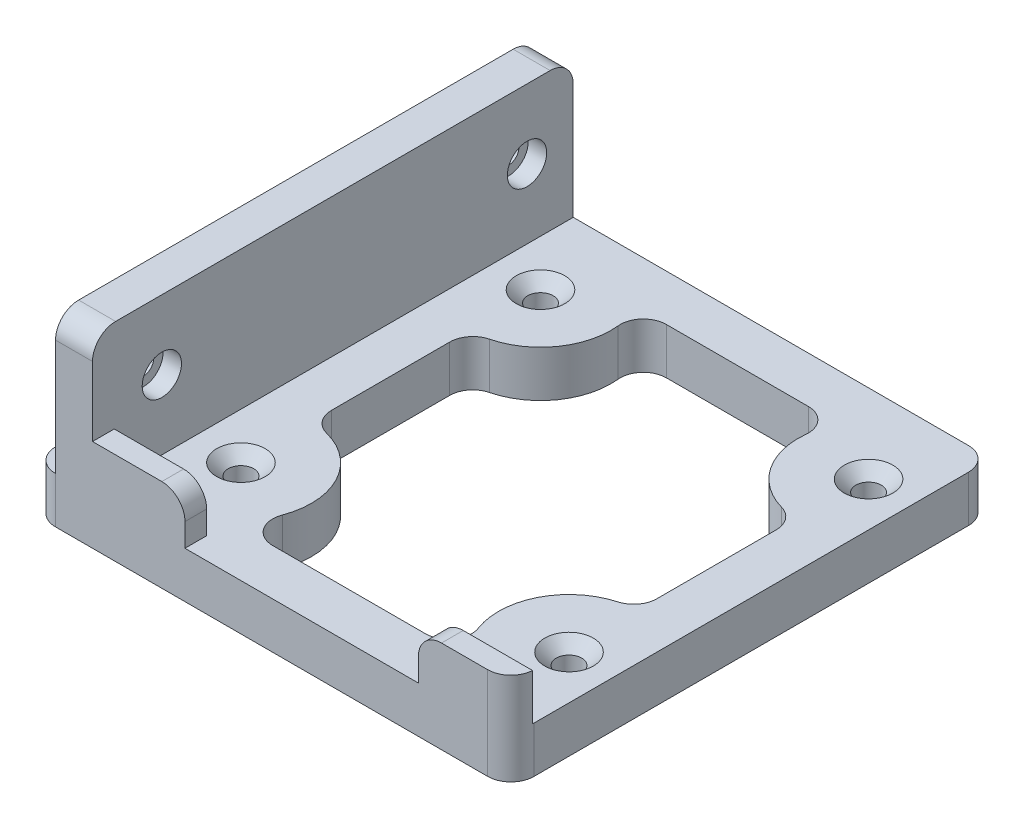
SolidWorks part; units mm, degrees
ref_plane "正面" through (0, 0, 0) normal (0, 0, 1) x (1, 0, 0)
ref_plane "平面" through (0, 0, 0) normal (0, 1, 0) x (1, 0, 0)
ref_plane "右側面" through (0, 0, 0) normal (1, 0, 0) x (0, 0, -1)
sketch "ｽｹｯﾁ1" plane through (0, 0, 0) normal (1, 0, 0) x (0, 0, -1)
  line L4 (0, 21.9) -> (0, -21.9) construction
  point P0 (0, 0)
  line B0 (49.5, -15.9) -> (49.5, 15.9)
  line B1 (-43.5, -21.9) -> (43.5, -21.9)
  line B2 (-49.5, 15.9) -> (-49.5, -15.9)
  line B3 (43.5, 21.9) -> (-43.5, 21.9)
  arc B4 (49.5, 15.9) -> (43.5, 21.9) centre (43.5, 15.9) ccw
  arc B5 (43.5, -21.9) -> (49.5, -15.9) centre (43.5, -15.9) ccw
  arc B6 (-49.5, -15.9) -> (-43.5, -21.9) centre (-43.5, -15.9) ccw
  arc B7 (-43.5, 21.9) -> (-49.5, 15.9) centre (-43.5, 15.9) ccw
sketch_block_instance "ﾌﾞﾛｯｸ2-1"
sketch_block "ﾌﾞﾛｯｸ2"
sketch "ｽｹｯﾁ2" plane through (0, 0, 0) normal (0, 1, 0) x (1, 0, 0)
  line L0 (-49, 48.5) -> (-49, -48.5)
  line L1 (40, 49.5) -> (-48, 49.5)
  line L2 (41, 48.5) -> (41, -48.5)
  line L3 (-49, 0) -> (41, 0) construction
  line L4 (-4, 49.5) -> (-4, -54.5) construction
  line L5 (40, -49.5) -> (-48, -49.5)
  line L6 (41, -43.5) -> (41, 43.5) construction
  line L7 (-39.485, 32.4) -> (31.485, 32.4) construction
  line L8 (-39.485, 32.4) -> (-39.485, -32.4) construction
  line L9 (-39.485, -32.4) -> (31.485, -32.4) construction
  line L10 (31.485, 32.4) -> (31.485, -32.4) construction
  line L11 (-49, -43.5) -> (-49, 43.5) construction
  line L12 (-37, 49.5) -> (-32.97, 49.5) construction
  line L13 (-41, -49.5) -> (-37, -49.5) construction
  line L14 (-48, -43.5) -> (-48, -49.5) construction
  line L15 (-49, -54.5) -> (41, -54.5) construction
  arc A0 (-49, -48.5) -> (-48, -49.5) centre (-48, -48.5) ccw
  arc A1 (-48, 49.5) -> (-49, 48.5) centre (-48, 48.5) ccw
  arc A2 (41, 48.5) -> (40, 49.5) centre (40, 48.5) ccw
  arc A3 (40, -49.5) -> (41, -48.5) centre (40, -48.5) ccw
  circle A4 centre (-39.485, 32.4) radius 2.65 construction
  circle A5 centre (31.485, 32.4) radius 2.65 construction
  arc A6 (41, 48.5) -> (40, 49.5) centre (40, 48.5) ccw construction
  arc A7 (-48, 49.5) -> (-49, 48.5) centre (-48, 48.5) ccw construction
  circle A8 centre (31.485, 32.4) radius 2.65
  circle A9 centre (31.485, -32.4) radius 2.65
  circle A10 centre (-39.485, -32.4) radius 2.65
  circle A11 centre (-39.485, 32.4) radius 2.65
  arc A12 (-49, -48.5) -> (-48, -49.5) centre (-48, -48.5) ccw construction
  arc A13 (40, -49.5) -> (41, -48.5) centre (40, -48.5) ccw construction
  point P3 (-4, 32.4)
  point P12 (-39.485, 0)
  point P47 (0, 0)
  dimension "D1" = 5.3
  dimension "D2" = 9.515
  dimension "D3" = 64.8
  dimension "D4" = 5
sketch "ｽｹｯﾁ3" plane through (0, 0, 0) normal (0, 0, 1) x (1, 0, 0)
  line L0 (-57.5, -6.9) -> (-49.5, -6.9) construction
  line L1 (-57.5, 8.1) -> (-49.5, 8.1)
  line L2 (-57.5, 8.1) -> (-57.5, -21.9)
  line L3 (-62.5, -31.9) -> (41, -31.9)
  line L4 (41, -21.9) -> (41, -31.9)
  line L6 (-49.5, 8.1) -> (-49.5, -21.9)
  line L7 (-49.5, -21.9) -> (41, -21.9)
  line L8 (-62.5, -21.9) -> (-57.5, -21.9)
  line L9 (-62.5, -21.9) -> (-62.5, -31.9)
  dimension "D1" = 0.5
  dimension "D2" = 0
  dimension "D3" = 10
  dimension "D4" = 8
  dimension "D5" = 40
  dimension "D6" = 30
  dimension "D7" = 5
extrude "ﾎﾞｽ - 押し出し1" add sketch "ｽｹｯﾁ3" against normal up to vertex (49.5 mm away) and the other way up to vertex (54.5 mm away) up to point (-4, 0, -49.5) other way up to point (-4, 0, 54.5)
sketch "ｽｹｯﾁ4" plane through (-49.5, 0, 0) normal (1, 0, 0) x (0, 0, -1)
  line L0 (-54.5, -6.9) -> (49.5, -6.9) construction
  line L2 (49.5, -21.9) -> (49.5, 8.1) construction
  line L4 (0, 8.1) -> (0, -21.9) construction
  line L7 (49.5, 8.1) -> (-54.5, 8.1) construction
  line L8 (49.5, -21.9) -> (-54.5, -21.9) construction
  circle A0 centre (-39.5, -6.9) radius 2.25
  circle A1 centre (39.5, -6.9) radius 2.25
  point P2 (0, 0)
  point P3 (0, 8.1)
  point P7 (0, 8.1)
  point P14 (0, 0)
  point P15 (0, -21.9)
  point P17 (0, 0)
  point P21 (0, -21.9)
  point P24 (-58.8943, -9.5686)
  point P26 (-39.5182, -6.9)
  dimension "D1" = 15
  dimension "D2" = 4.5
  dimension "D3" = 15
extrude "ｶｯﾄ - 押し出し1" cut sketch "ｽｹｯﾁ4" against normal through all
sketch "ｽｹｯﾁ5" plane through (-49.5, 0, 0) normal (1, 0, 0) x (0, 0, -1)
  circle A0 centre (-39.5, -6.9) radius 4.25
  circle A1 centre (39.5, -6.9) radius 4.25
  dimension "D1" = 8.5
extrude "ｶｯﾄ - 押し出し2" cut sketch "ｽｹｯﾁ5" against normal blind 4
sketch "ｽｹｯﾁ6" plane through (0, -21.9, 0) normal (0, 1, 0) x (1, 0, 0)
  circle A0 centre (-39.485, 32.4) radius 2.75
  circle A1 centre (31.485, 32.4) radius 2.75
  circle A2 centre (31.485, -32.4) radius 2.75
  circle A3 centre (-39.485, -32.4) radius 2.75
  dimension "D1" = 5.5
extrude "ｶｯﾄ - 押し出し3" cut sketch "ｽｹｯﾁ6" against normal through all
chamfer "面取り1" distance 2.5 angle 45 4 edges at (31.485, -21.9, 35.15) (-39.485, -21.9, 35.15) (31.485, -21.9, -29.65) (-39.485, -21.9, -29.65)
sketch "ｽｹｯﾁ7" plane through (0, -21.9, 0) normal (0, 1, 0) x (1, 0, 0)
  line L4 (31, -44.5) -> (31, 39.5)
  line L5 (31, -44.5) -> (31, 39.5)
  line L6 (-39.5, 39.5) -> (-39.5, -44.5)
  line L7 (-39.5, 39.5) -> (-39.5, -44.5)
  line L25 (31, 39.5) -> (-39.5, 39.5)
  line L27 (-39.5, -44.5) -> (31, -44.5)
  line L29 (31, 39.5) -> (-39.5, 39.5)
  line L31 (-39.5, -44.5) -> (31, -44.5)
  circle A5 centre (-39.485, 32.4) radius 15.25
  circle A6 centre (-39.485, 32.4) radius 15.25
  circle A8 centre (31.485, 32.4) radius 15.25
  circle A9 centre (31.485, 32.4) radius 15.25
  circle A11 centre (-39.485, -32.4) radius 15.25
  circle A12 centre (-39.485, -32.4) radius 15.25
  circle A14 centre (31.485, -32.4) radius 15.25
  circle A15 centre (31.485, -32.4) radius 15.25
  dimension "D1" = 10
  dimension "D2" = 10
  dimension "D3" = 10
  dimension "D4" = 10
  dimension "D5" = 10
extrude "ｶｯﾄ - 押し出し4" cut sketch "ｽｹｯﾁ7" against normal through all contours A15 L5 A9 L29 A6 L7 A12 L31
sketch "ｽｹｯﾁ10" plane through (0, -21.9, 0) normal (0, 1, 0) x (1, 0, 0)
  line L0 (40, -49.5) -> (-48, -49.5) construction
  line L1 (41, -54.5) -> (-49.5, -54.5)
  line L2 (41, -54.5) -> (41, -49.8)
  line L3 (41, -49.8) -> (-49.5, -49.8)
  line L4 (-49.5, -54.5) -> (-49.5, -49.8)
  line L5 (-49.5, 49.5) -> (-49.5, -54.5) construction
  line L6 (-29.5, -49.8) -> (-29.5, -54.5)
  line L7 (-4.25, -49.8) -> (-4.25, -54.5) construction
  line L8 (21, -49.8) -> (21, -54.5)
  line L9 (41, -54.5) -> (-49.5, -54.5) construction
  point P15 (11.168, -49.8)
  point P16 (11.168, -54.5)
  line M7 (-49.5, 49.5) -> (-49.5, -54.5)
  line M8 (-49.5, -54.5) -> (41, -54.5)
  line M9 (41, -54.5) -> (41, 49.5)
  dimension "D1" = 0.3
  dimension "D2" = 20
extrude "ﾎﾞｽ - 押し出し2" add sketch "ｽｹｯﾁ10" along normal blind 10 contours L6 L3 M7 M8 | L3 L8 M8 M9
fillet "ﾌｨﾚｯﾄ1" radius 5 19 edges at (-62.5, -26.9, -49.5) (31, -26.9, 17.1577) (22.2032, -26.9, 44.5) (-30.2032, -26.9, 44.5) (-39.5, -26.9, 17.15) (-39.5, -26.9, -17.15) (-25.9886, -26.9, -39.5) (17.9886, -26.9, -39.5) (31, -26.9, -17.1577) (-29.5, -11.9, 52.15) (41, -16.9, 49.8) (21, -11.9, 52.15) (41, -11.9, 52.15) (41, -26.9, -49.5) (-60, -21.9, 54.5) (-62.5, -26.9, 54.5) (41, -21.9, 54.5) (-53.5, 8.1, 54.5) (-53.5, 8.1, -49.5)
